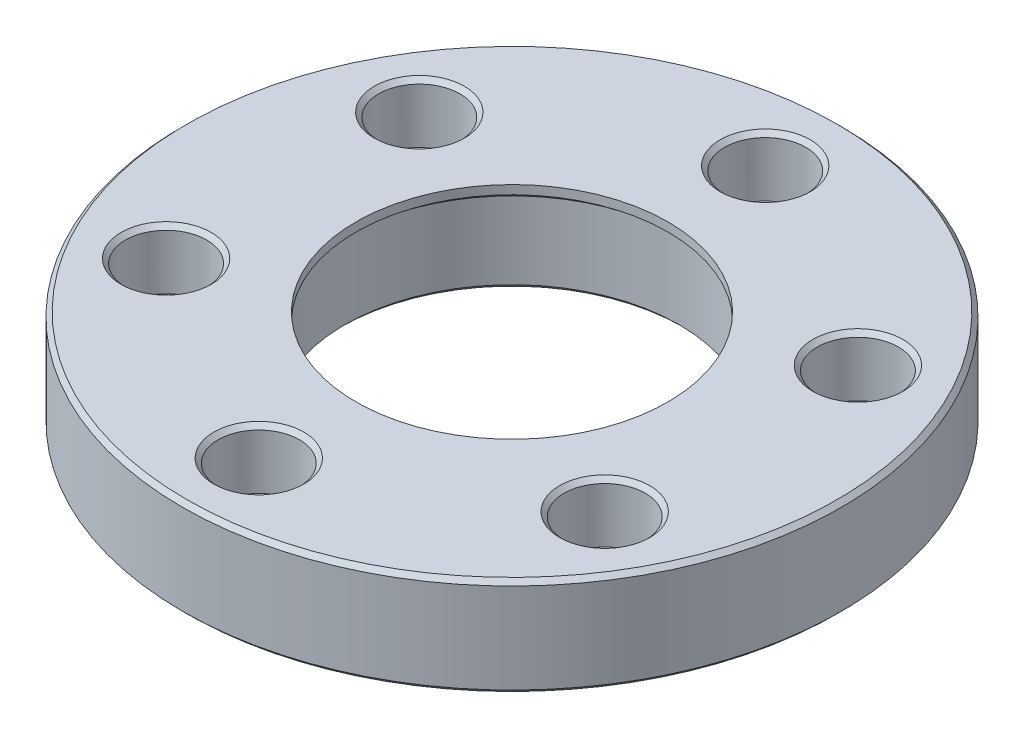
SolidWorks part; units mm, degrees
ref_plane "前视基准面" through (0, 0, 0) normal (0, 0, 1) x (1, 0, 0)
ref_plane "上视基准面" through (0, 0, 0) normal (0, 1, 0) x (1, 0, 0)
ref_plane "右视基准面" through (0, 0, 0) normal (1, 0, 0) x (0, 0, -1)
other "Configuration Table"
sketch "草图1" plane through (0, 0, 0) normal (0, 1, 0) x (1, 0, 0)
  circle A0 centre (0, 0) radius 7.1
  circle A1 centre (0, 0) radius 15
  circle A2 centre (0, 0) radius 11.525 construction
  circle A3 centre (0, 11.525) radius 1.85
  circle A4 centre (9.9809, 5.7625) radius 1.85
  circle A5 centre (9.9809, -5.7625) radius 1.85
  circle A6 centre (0, -11.525) radius 1.85
  circle A7 centre (-9.9809, -5.7625) radius 1.85
  circle A8 centre (-9.9809, 5.7625) radius 1.85
  point P19 (0, 0)
  dimension "D1" = 14.2
  dimension "D2" = 30
  dimension "D3" = 23.05
  dimension "D4" = 3.7
  dimension "D5" = 6
extrude "凸台-拉伸1" add sketch "草图1" along normal blind 2.7
sketch "草图2" plane through (0, 0, 0) normal (0, -1, 0) x (-1, 0, 0)
  circle A0 centre (0, 0) radius 7.1 construction
  circle A1 centre (0, 0) radius 15 construction
  circle A2 centre (0, 0) radius 7.1
  circle A3 centre (0, 0) radius 15
  circle A4 centre (0, 11.53) radius 0.9
  circle A6 centre (0, 0) radius 11.53 construction
  circle A7 centre (9.9853, 5.765) radius 0.9
  circle A8 centre (9.9853, -5.765) radius 0.9
  circle A9 centre (0, -11.53) radius 0.9
  circle A10 centre (-9.9853, -5.765) radius 0.9
  circle A11 centre (-9.9853, 5.765) radius 0.9
  point P21 (0, 0)
  dimension "D1" = 1.8
  dimension "D2" = 23.06
  dimension "D3" = 6
extrude "凸台-拉伸2" add sketch "草图2" along normal blind 1.8
sketch "草图3" plane through (0, -1.8, 0) normal (0, -1, 0) x (-1, 0, 0)
  circle A0 centre (0, 0) radius 7.6
  dimension "D1" = 15.2
extrude "切除-拉伸1" cut sketch "草图3" against normal blind 4.1
chamfer "倒角1" distance 0.2 angle 45 15 edges at (0, -1.8, -15) (-9.9809, 2.7, -3.9125) (0, 2.7, 13.375) (9.9809, 2.7, -3.9125) (0, 2.7, 15) (0, 2.7, -9.675) (9.9809, 2.7, 7.6125) (-9.9809, 2.7, 7.6125) (9.9853, -1.8, -6.665) (0, -1.8, 10.63) (-9.9853, -1.8, -6.665) (0, -1.8, -12.43) (-9.9853, -1.8, 4.865) (9.9853, -1.8, 4.865) (0, -1.8, -7.6)
chamfer "倒角2" distance 0.4 angle 45 1 edges at (0, 2.3, -7.6)
